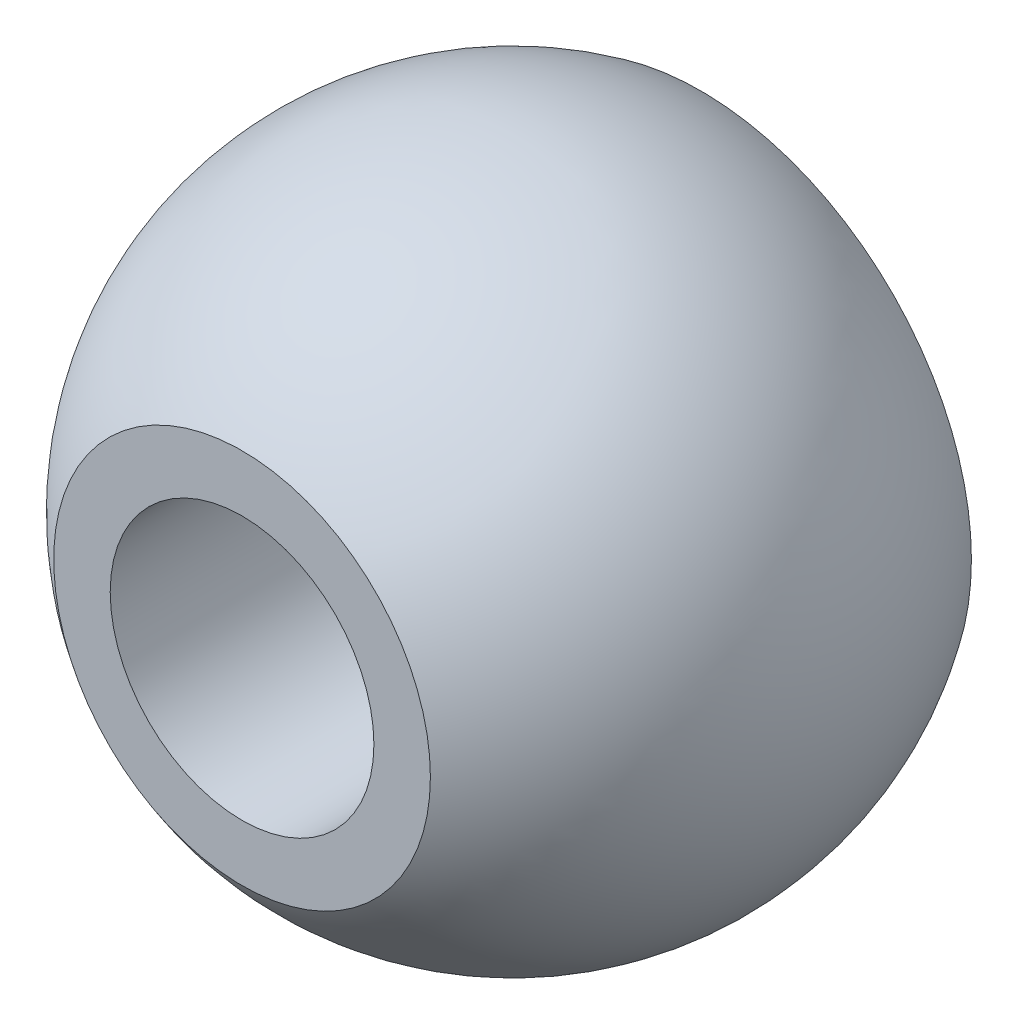
SolidWorks part; units mm, degrees
ref_plane "Front Plane" through (0, 0, 0) normal (0, 0, 1) x (1, 0, 0)
ref_plane "Top Plane" through (0, 0, 0) normal (0, 1, 0) x (1, 0, 0)
ref_plane "Right Plane" through (0, 0, 0) normal (1, 0, 0) x (0, 0, -1)
sketch "Sketch1" plane through (0, 0, 0) normal (0, 1, 0) x (1, 0, 0)
  line L0 (88.3084, 0) -> (86.1, 0)
  line L1 (86.1, 0) -> (86.1, -7.3084)
  line L2 (86.1, -7.3084) -> (87, -7.3084)
  line L3 (84, 0) -> (84, -7.3084) construction
  arc A0 (87, -7.3084) -> (88.3084, 0) centre (84, -3) ccw
revolve "Revolve1" add sketch "Sketch1" angle 360 about L3
